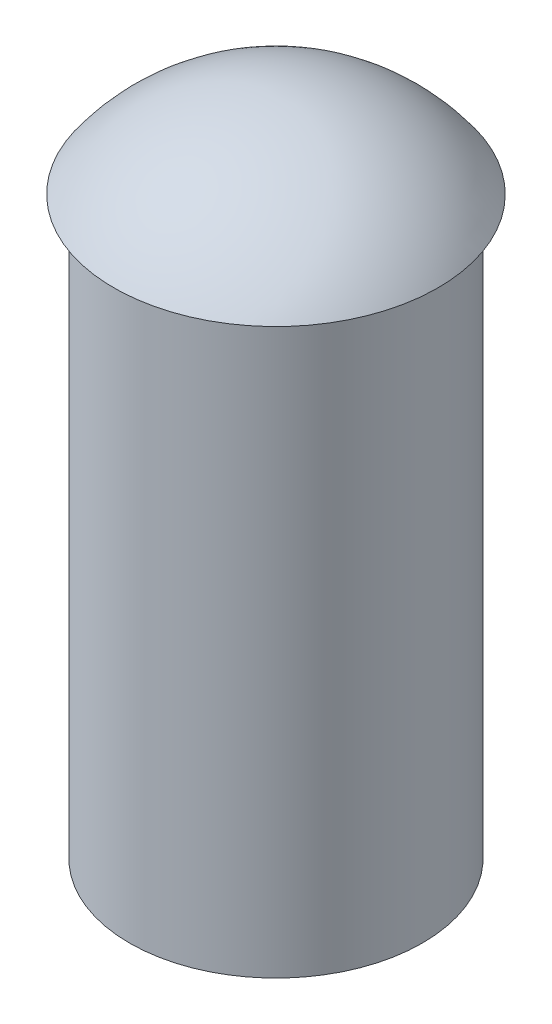
SolidWorks part; units mm, degrees
material "ABS PC"
ref_plane "Front Plane" through (0, 0, 0) normal (0, 0, 1) x (1, 0, 0)
ref_plane "Top Plane" through (0, 0, 0) normal (0, 1, 0) x (1, 0, 0)
ref_plane "Right Plane" through (0, 0, 0) normal (1, 0, 0) x (0, 0, -1)
sketch "Sketch2" plane through (0, 0, 0) normal (0, 1, 0) x (1, 0, 0)
  circle A0 centre (0, 0) radius 1.4
  dimension "D1" = 2.8
extrude "Boss-Extrude1" add sketch "Sketch2" against normal blind 5.5
sketch "Sketch4" plane through (0, 0, 0) normal (1, 0, 0) x (0, 0, -1)
  line L0 (0, 0) -> (-1.55, 0)
  line L3 (0, 0) -> (0, 0.8)
  arc A0 (0, 0.8) -> (-1.55, 0) centre (0, -1.1016) ccw
  dimension "D1" = 0.8
  dimension "D2" = 1.55
revolve "Revolve1" add sketch "Sketch4" angle 360 about L3
equation "\"LENGTH\"=5.5"
equation "\"D1@Boss-Extrude1\"=\"LENGTH\""
equation "\"D2@Sketch4\"=3.1/2"
